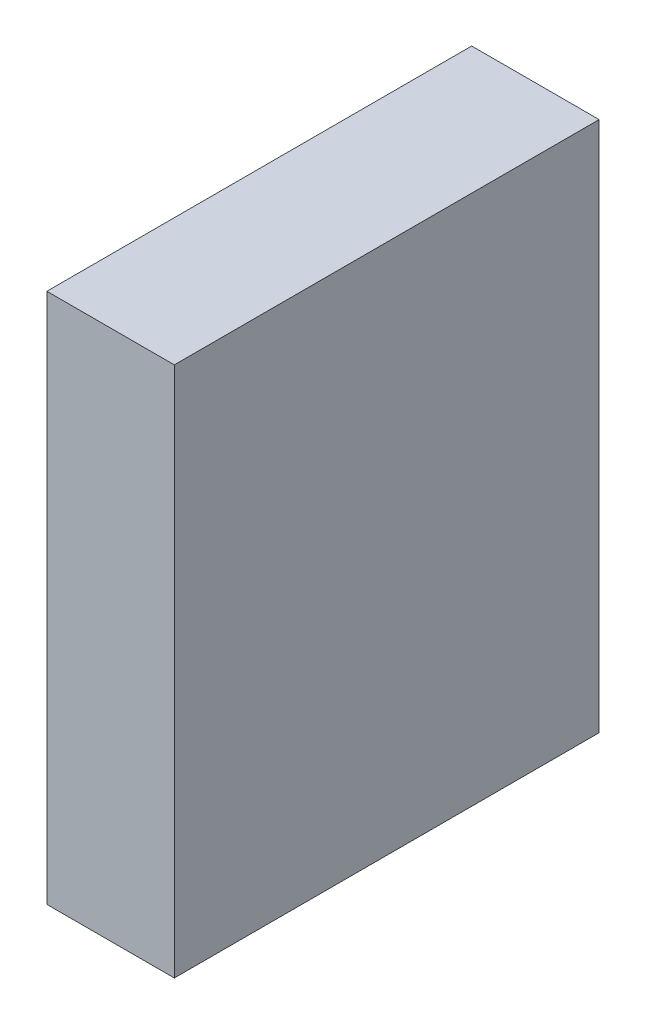
SolidWorks part; units mm, degrees
ref_plane "Front Plane" through (0, 0, 0) normal (0, 0, 1) x (1, 0, 0)
ref_plane "Top Plane" through (0, 0, 0) normal (0, 1, 0) x (1, 0, 0)
ref_plane "Right Plane" through (0, 0, 0) normal (1, 0, 0) x (0, 0, -1)
sketch "Sketch1" plane through (0, 0, 0) normal (1, 0, 0) x (0, 0, -1)
  line L1 (50, -62.5) -> (-50, -62.5)
  line L2 (50, -62.5) -> (50, 62.5)
  line L3 (50, 62.5) -> (-50, 62.5)
  line L4 (-50, -62.5) -> (-50, 62.5)
  line L5 (50, -62.5) -> (-50, 62.5) construction
  line L6 (50, 62.5) -> (-50, -62.5) construction
  point P0 (0, 0)
  dimension "D1" = 100
  dimension "D2" = 125
extrude "Boss-Extrude1" add sketch "Sketch1" along normal mid plane 30
